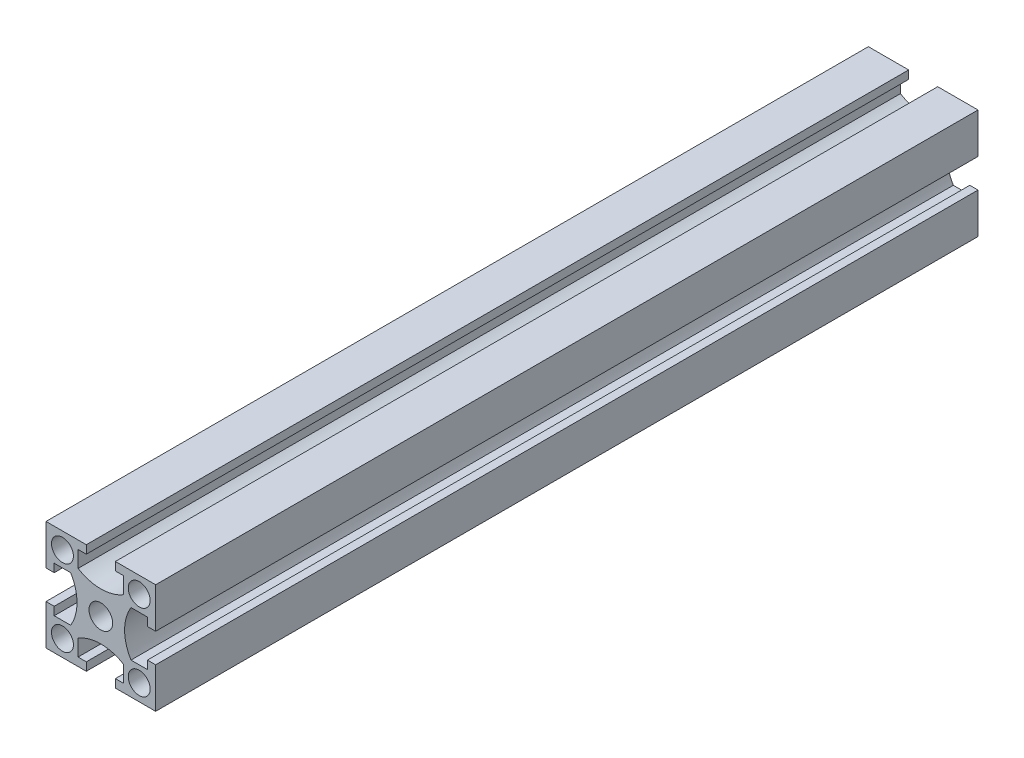
SolidWorks part; units mm, degrees
ref_plane "정면" through (0, 0, 0) normal (0, 0, 1) x (1, 0, 0)
ref_plane "윗면" through (0, 0, 0) normal (0, 1, 0) x (1, 0, 0)
ref_plane "우측면" through (0, 0, 0) normal (1, 0, 0) x (0, 0, -1)
sketch "스케치1" plane through (0, 0, 0) normal (0, 0, 1) x (1, 0, 0)
  line L1 (-10, 10) -> (10, 10)
  line L2 (-10, 10) -> (-10, -10)
  line L3 (-10, -10) -> (10, -10)
  line L4 (10, 10) -> (10, -10)
  line L5 (-10, 10) -> (10, -10) construction
  line L6 (-10, -10) -> (10, 10) construction
  point P0 (0, 0)
  dimension "D1" = 20
  dimension "D2" = 20
extrude "보스-돌출1" add sketch "스케치1" along normal blind 150
sketch "스케치2" plane through (0, 0, 150) normal (0, 0, 1) x (1, 0, 0)
  line L0 (-2.65, 10) -> (-2.65, 8.5)
  line L1 (10, 10) -> (-10, 10) construction
  line L2 (-2.65, 8.5) -> (-4.15, 8.5)
  line L3 (-4.15, 8.5) -> (-4.15, 5.5)
  line L4 (-2.65, 10) -> (2.65, 10)
  line L5 (2.65, 10) -> (2.65, 8.5)
  line L6 (2.65, 8.5) -> (4.15, 8.5)
  line L7 (4.15, 8.5) -> (4.15, 5.5)
  line L8 (10, 2.65) -> (8.5, 2.65)
  line L9 (8.5, 2.65) -> (8.5, 4.15)
  line L10 (8.5, 4.15) -> (5.5, 4.15)
  line L11 (10, 2.65) -> (10, -2.65)
  line L12 (10, -2.65) -> (8.5, -2.65)
  line L13 (8.5, -2.65) -> (8.5, -4.15)
  line L14 (8.5, -4.15) -> (5.5, -4.15)
  line L15 (2.65, -10) -> (2.65, -8.5)
  line L16 (2.65, -8.5) -> (4.15, -8.5)
  line L17 (4.15, -8.5) -> (4.15, -5.5)
  line L18 (2.65, -10) -> (-2.65, -10)
  line L19 (-2.65, -10) -> (-2.65, -8.5)
  line L20 (-2.65, -8.5) -> (-4.15, -8.5)
  line L21 (-4.15, -8.5) -> (-4.15, -5.5)
  line L22 (-10, -2.65) -> (-8.5, -2.65)
  line L23 (-8.5, -2.65) -> (-8.5, -4.15)
  line L24 (-8.5, -4.15) -> (-5.5, -4.15)
  line L25 (-10, -2.65) -> (-10, 2.65)
  line L26 (-10, 2.65) -> (-8.5, 2.65)
  line L27 (-8.5, 2.65) -> (-8.5, 4.15)
  line L28 (-8.5, 4.15) -> (-5.5, 4.15)
  arc A1 (-4.15, 5.5) -> (4.15, 5.5) centre (0, 12.3394) ccw
  arc A2 (5.5, 4.15) -> (5.5, -4.15) centre (12.3394, 0) ccw
  arc A3 (4.15, -5.5) -> (-4.15, -5.5) centre (0, -12.3394) ccw
  arc A4 (-5.5, -4.15) -> (-5.5, 4.15) centre (-12.3394, 0) ccw
  circle A5 centre (0, 0) radius 2.15
  circle A6 centre (-7, 7) radius 2
  circle A7 centre (7, 7) radius 2
  circle A8 centre (7, -7) radius 2
  circle A9 centre (-7, -7) radius 2
  point P4 (-2.65, 9.25)
  point P43 (0, 0)
  dimension "D2" = 1.5
  dimension "D8" = 4.3
  dimension "D9" = 4
  dimension "D10" = 4
  dimension "D11" = 4
  dimension "D12" = 4
  dimension "D21" = 8
  dimension "D1" = 5.3
  dimension "D3" = 8.3
  dimension "D4" = 4.15
  dimension "D5" = 2.65
  dimension "D6" = 4
  dimension "D7" = 3
  dimension "D13" = 14
  dimension "D14" = 7
  dimension "D15" = 7
  dimension "D16" = 7
  dimension "D17" = 14
  dimension "D18" = 7
  dimension "D19" = 7
  dimension "D20" = 7
extrude "컷-돌출1" cut sketch "스케치2" against normal blind 300
